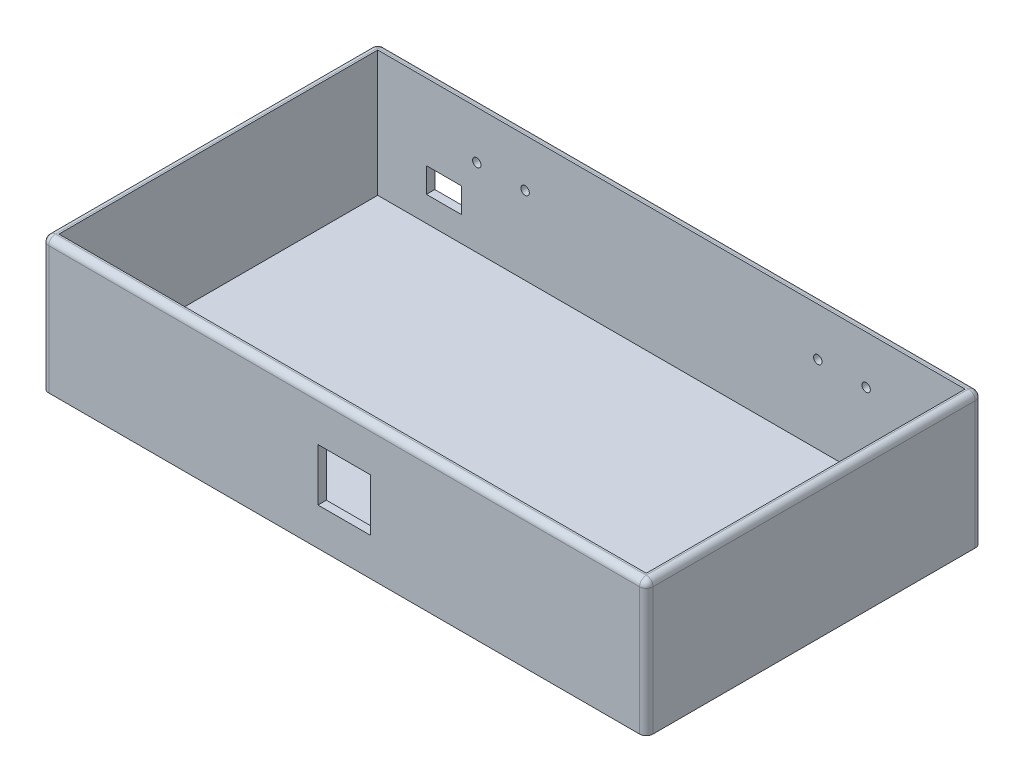
SolidWorks part; units mm, degrees
other "Camera1"
ref_plane "Front Plane" through (0, 0, 0) normal (0, 0, 1) x (1, 0, 0)
ref_plane "Top Plane" through (0, 0, 0) normal (0, 1, 0) x (1, 0, 0)
ref_plane "Right Plane" through (0, 0, 0) normal (1, 0, 0) x (0, 0, -1)
sketch "Sketch1" plane through (0, 0, 0) normal (0, 1, 0) x (1, 0, 0)
  line L1 (228.6, -127) -> (-228.6, -127)
  line L2 (228.6, -127) -> (228.6, 127)
  line L3 (228.6, 127) -> (-228.6, 127)
  line L4 (-228.6, -127) -> (-228.6, 127)
  line L5 (228.6, -127) -> (-228.6, 127) construction
  line L6 (228.6, 127) -> (-228.6, -127) construction
  point P0 (0, 0)
  dimension "D1" = 254
  dimension "D2" = 457.2
extrude "Boss-Extrude1" add sketch "Sketch1" along normal blind 101.6
shell "Shell1" thickness 6.35
fillet "Fillet1" radius 5.08 8 edges at (228.6, 101.6, 0) (0, 101.6, -127) (-228.6, 101.6, 0) (0, 101.6, 127) (228.6, 50.8, -127) (228.6, 50.8, 127) (-228.6, 50.8, -127) (-228.6, 50.8, 127)
sketch "Sketch3" plane through (0, 0, 127) normal (0, 0, 1) x (1, 0, 0)
  line L0 (-223.52, 96.52) -> (223.52, 0) construction
  line L2 (-19.812, 28.448) -> (19.812, 28.448)
  line L3 (-19.812, 28.448) -> (-19.812, 68.072)
  line L4 (-19.812, 68.072) -> (19.812, 68.072)
  line L5 (19.812, 28.448) -> (19.812, 68.072)
  line L6 (-19.812, 28.448) -> (19.812, 68.072) construction
  line L7 (-19.812, 68.072) -> (19.812, 28.448) construction
  point P5 (0, 48.26)
  dimension "D1" = 39.624
  dimension "D2" = 39.624
extrude "Cut-Extrude1" cut sketch "Sketch3" against normal up to next
sketch "Sketch6" plane through (0, 0, -127) normal (0, 0, -1) x (-1, 0, 0)
  line L0 (223.52, 0) -> (223.52, 96.52) construction
  line L1 (0, 55.88) -> (0, -55.88) construction
  line L2 (-223.52, 101.6) -> (223.52, 101.6) construction
  circle A0 centre (147.32, 65.278) radius 3.175
  circle A1 centre (110.744, 65.278) radius 3.175
  circle A2 centre (-147.32, 65.278) radius 3.175
  circle A3 centre (-110.744, 65.278) radius 3.175
  point P4 (223.52, 48.26)
  point P5 (0, 0)
  point P6 (147.32, 65.278)
  point P8 (0, 0)
  point P12 (123.8175, 65.278)
  dimension "D1" = 76.2
  dimension "D2" = 36.322
  dimension "D3" = 36.576
extrude "Cut-Extrude3" cut sketch "Sketch6" against normal up to next contours A0 | A1 | A3 | A2
sketch "Sketch7" plane through (0, 0, -127) normal (0, 0, -1) x (-1, 0, 0)
  line L0 (223.52, 0) -> (223.52, 96.52) construction
  line L1 (185.42, 25.4) -> (158.75, 25.4)
  line L2 (185.42, 25.4) -> (185.42, 44.196)
  line L3 (185.42, 44.196) -> (158.75, 44.196)
  line L4 (158.75, 25.4) -> (158.75, 44.196)
  line L5 (-223.52, 0) -> (223.52, 0) construction
  dimension "D1" = 18.796
  dimension "D2" = 26.67
  dimension "D3" = 38.1
  dimension "D4" = 25.4
extrude "Cut-Extrude4" cut sketch "Sketch7" against normal up to next contours L3 L4 L1 L2
